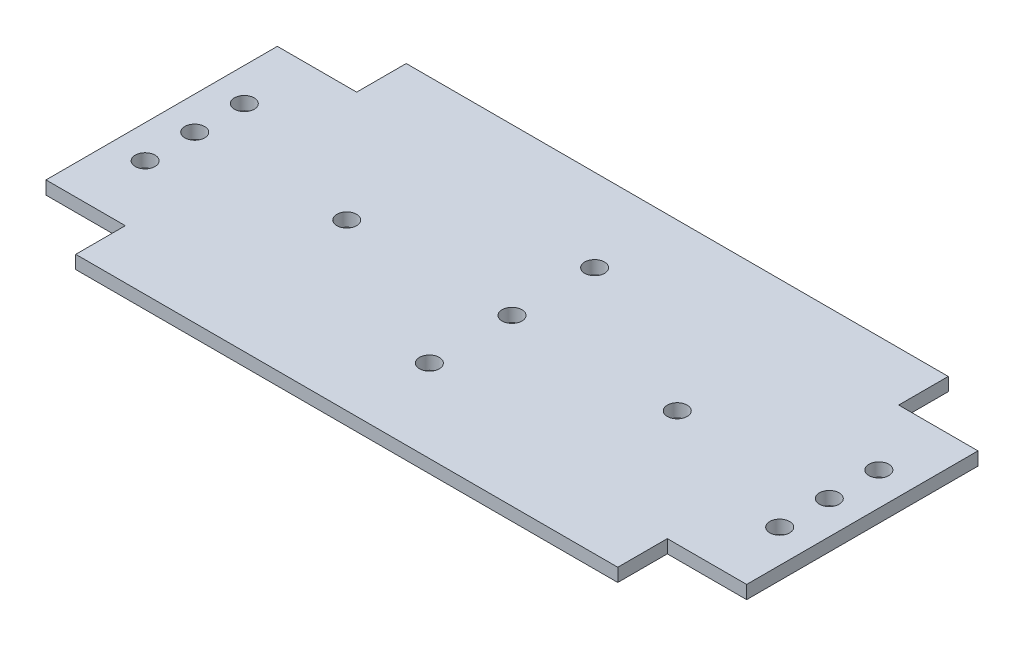
SolidWorks part; units mm, degrees
ref_plane "Alzado" through (0, 0, 0) normal (0, 0, 1) x (1, 0, 0)
ref_plane "Planta" through (0, 0, 0) normal (0, 1, 0) x (1, 0, 0)
ref_plane "Vista lateral" through (0, 0, 0) normal (1, 0, 0) x (0, 0, -1)
sketch "Croquis1" plane through (0, 0, 0) normal (0, 1, 0) x (1, 0, 0)
  line L0 (-82, -35) -> (-82, -50)
  line L1 (-82, 50) -> (82, 50)
  line L2 (-82, 50) -> (-82, 35)
  line L3 (-82, -50) -> (82, -50)
  line L4 (82, 50) -> (82, 35)
  line L5 (-82, 50) -> (82, -50) construction
  line L6 (-82, -50) -> (82, 50) construction
  line L8 (-106, -35) -> (-106, 35)
  line L9 (106, -35) -> (106, 35)
  line L10 (106, 35) -> (82, 35)
  line L11 (106, -35) -> (82, -35)
  line L12 (-106, 35) -> (-82, 35)
  line L13 (-106, -35) -> (-82, -35)
  line L14 (82, -35) -> (82, -50)
  point P0 (0, 0)
  point P13 (-106, 0)
  point P16 (106, 0)
  dimension "D1" = 100
  dimension "D2" = 164
  dimension "D3" = 24
  dimension "D4" = 24
  dimension "D5" = 70
  dimension "D6" = 70
extrude "Saliente-Extruir1" add sketch "Croquis1" along normal blind 4
sketch "Croquis2" plane through (0, 4, 0) normal (0, 1, 0) x (1, 0, 0)
  line L0 (-82, 35) -> (-106, 35) construction
  line L2 (-82, 35) -> (-82, -35)
  line L3 (-106, -35) -> (-82, -35) construction
  circle A0 centre (-96, 0) radius 3
  circle A1 centre (-96, 15) radius 3
  circle A2 centre (-96, -15) radius 3
  dimension "D3" = 6
  dimension "D7" = 6
  dimension "D9" = 6
  dimension "D1" = 14
  dimension "D2" = 20
  dimension "D4" = 20
extrude "Cortar-Extruir1" cut sketch "Croquis2" against normal blind 4
sketch "Croquis3" plane through (0, 4, 0) normal (0, 1, 0) x (1, 0, 0)
  line L0 (82, 35) -> (82, -35)
  line L1 (82, 0) -> (90, 0)
  line L3 (106, 35) -> (82, 35) construction
  line L5 (90, 0) -> (102, 0) construction
  line L6 (82, -35) -> (106, -35) construction
  circle A0 centre (96, 0) radius 3
  circle A1 centre (96, 15) radius 3
  circle A2 centre (96, -15) radius 3
  dimension "D3" = 6
  dimension "D5" = 6
  dimension "D8" = 6
  dimension "D2" = 14
  dimension "D4" = 20
  dimension "D6" = 20
  dimension "D1" = 8
extrude "Cortar-Extruir2" cut sketch "Croquis3" against normal blind 4 contours A1 | A2 | A0
sketch "Croquis4" plane through (0, 4, 0) normal (0, 1, 0) x (1, 0, 0)
  line L0 (0, 50) -> (0, -50) construction
  line L1 (82, 50) -> (-82, 50) construction
  line L2 (-82, -50) -> (82, -50) construction
  line L3 (-50, 0) -> (50, 0)
  line L4 (0, -25) -> (0, 25)
  circle A0 centre (0, 0) radius 3
  circle A1 centre (-50, 0) radius 3
  circle A2 centre (50, 0) radius 3
  circle A3 centre (0, 25) radius 3
  circle A4 centre (0, -25) radius 3
  point P10 (0, 0)
  point P17 (0, 0)
  dimension "D2" = 6
  dimension "D3" = 6
  dimension "D4" = 6
  dimension "D6" = 6
  dimension "D7" = 6
  dimension "D1" = 100
  dimension "D5" = 50
extrude "Cortar-Extruir3" cut sketch "Croquis4" against normal up to surface (4 mm away)
